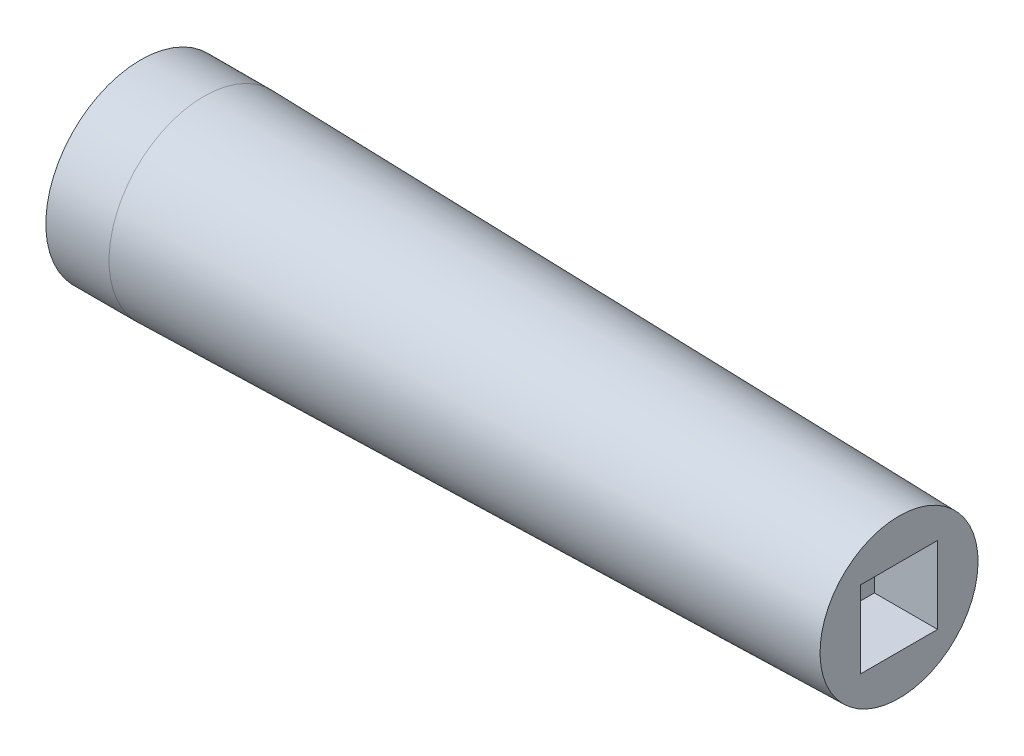
SolidWorks part; units mm, degrees
ref_plane "Front Plane" through (0, 0, 0) normal (0, 0, 1) x (1, 0, 0)
ref_plane "Top Plane" through (0, 0, 0) normal (0, 1, 0) x (1, 0, 0)
ref_plane "Right Plane" through (0, 0, 0) normal (1, 0, 0) x (0, 0, -1)
sketch "Sketch1" plane through (0, 0, 0) normal (0, 0, 1) x (1, 0, 0)
  line L0 (0, 15.875) -> (0, 0)
  line L1 (0, 0) -> (-152.4, 0)
  line L2 (-152.4, 0) -> (-152.4, 19.05)
  line L4 (-152.4, 19.05) -> (-139.7, 19.05)
  line L5 (-139.7, 19.05) -> (0, 15.875)
  dimension "D1" = 15.875
  dimension "D2" = 19.05
  dimension "D3" = 152.4
  dimension "D4" = 12.7
revolve "Revolve1" add sketch "Sketch1" angle 360 about L1
sketch "Sketch2" plane through (0, 0, 0) normal (1, 0, 0) x (0, 0, -1)
  line L1 (-7.747, -7.747) -> (7.747, -7.747)
  line L2 (-7.747, -7.747) -> (-7.747, 7.747)
  line L3 (-7.747, 7.747) -> (7.747, 7.747)
  line L4 (7.747, -7.747) -> (7.747, 7.747)
  line L5 (-7.747, -7.747) -> (7.747, 7.747) construction
  line L6 (-7.747, 7.747) -> (7.747, -7.747) construction
  point P0 (0, 0)
  dimension "D1" = 15.494
  dimension "D2" = 15.494
extrude "Cut-Extrude1" cut sketch "Sketch2" against normal blind 12.7
